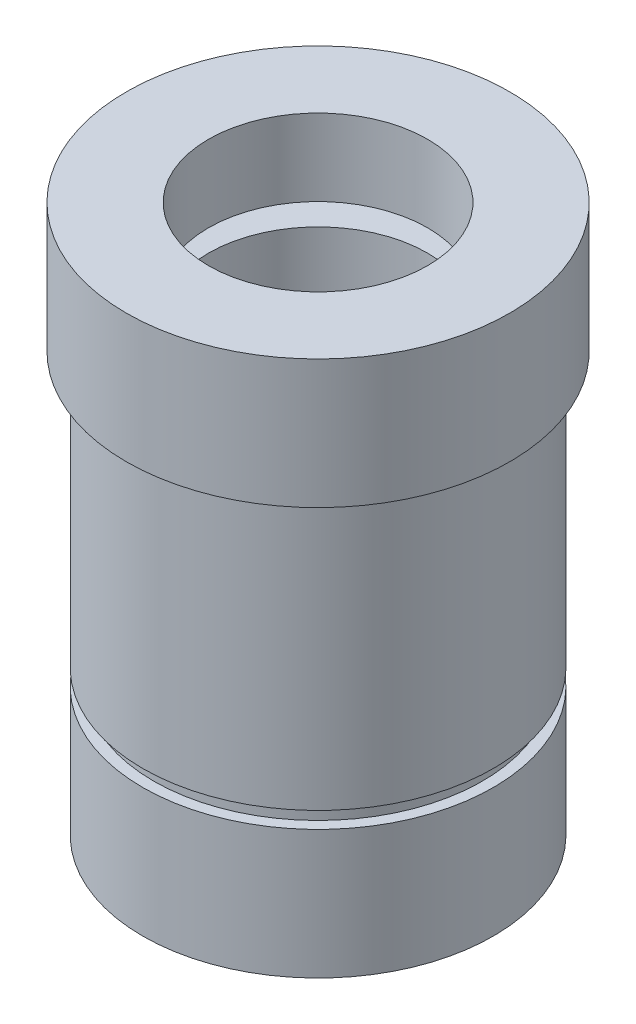
SolidWorks part; units mm, degrees
material "Beryllium S-200F, Vacuum Hot Pressed"
ref_plane "Front Plane" through (0, 0, 0) normal (0, 0, 1) x (1, 0, 0)
ref_plane "Top Plane" through (0, 0, 0) normal (0, 1, 0) x (1, 0, 0)
ref_plane "Right Plane" through (0, 0, 0) normal (1, 0, 0) x (0, 0, -1)
sketch "Sketch1" plane through (0, 0, 0) normal (0, 0, 1) x (1, 0, 0)
  line L0 (0, 23.3627) -> (0, -31.0453) construction
  line L1 (0, 23.1321) -> (17.5, 23.1321)
  line L2 (17.5, 23.1321) -> (17.5, 11.3821)
  line L3 (17.5, 11.3821) -> (16, 11.3821)
  line L4 (16, 11.3821) -> (16, -13.6179)
  line L5 (16, -13.6179) -> (15, -13.6179)
  line L6 (15, -13.6179) -> (15, -15.1179)
  line L7 (15, -15.1179) -> (16, -15.1179)
  line L8 (16, -15.1179) -> (16, -26.8679)
  line L9 (16, -26.8679) -> (0, -26.8679)
  line L10 (0, -26.8679) -> (0, 23.1321)
  point P12 (0.7282, -13.6895)
  point P14 (0, 0)
  point P15 (13.4894, -13.6179)
  dimension "D1" = 50
  dimension "D2" = 11.75
  dimension "D3" = 11.75
  dimension "D4" = 25
  dimension "D5" = 1.5
  dimension "D6" = 17.5
  dimension "D7" = 16
  dimension "D8" = 1.5
  dimension "D9" = 1
revolve "Revolve1" add sketch "Sketch1" angle 360 about L0
sketch "Sketch2" plane through (0, 23.1321, 0) normal (0, 1, 0) x (1, 0, 0)
  circle A0 centre (0, 0) radius 10
  dimension "D1" = 20
extrude "Cut-Extrude1" cut sketch "Sketch2" against normal through all
ref_plane "Plane1" through (0, 16.1321, 0) normal (0, 1, 0) x (1, 0, 0)
sketch "Sketch3" plane through (0, 16.1321, 0) normal (0, 1, 0) x (1, 0, 0)
  circle A0 centre (0, 0) radius 13
  dimension "D1" = 26
extrude "Cut-Extrude2" cut sketch "Sketch3" against normal blind 2
ref_plane "Plane2" through (0, -19.8679, 0) normal (0, -1, 0) x (-1, 0, 0)
sketch "Sketch4" plane through (0, -19.8679, 0) normal (0, -1, 0) x (-1, 0, 0)
  circle A0 centre (0, 0) radius 13
  dimension "D1" = 26
extrude "Cut-Extrude3" cut sketch "Sketch4" against normal blind 2
